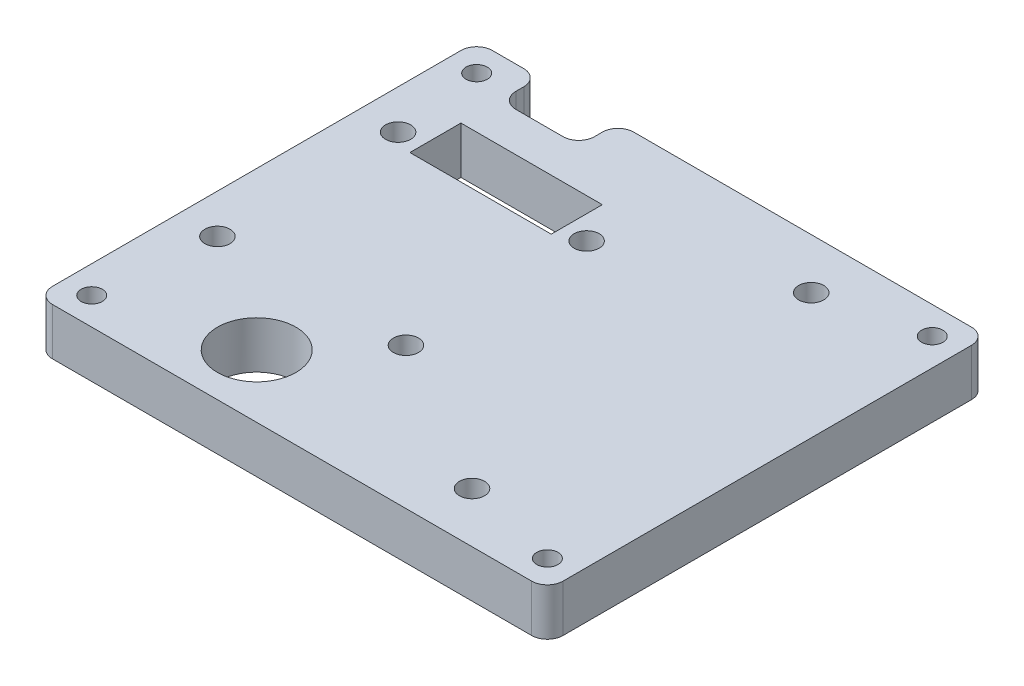
SolidWorks part; units mm, degrees
ref_plane "前视基准面" through (0, 0, 0) normal (0, 0, 1) x (1, 0, 0)
ref_plane "上视基准面" through (0, 0, 0) normal (0, 1, 0) x (1, 0, 0)
ref_plane "右视基准面" through (0, 0, 0) normal (1, 0, 0) x (0, 0, -1)
other "Configuration Table"
sketch "草图1" plane through (0, 0, 0) normal (0, 1, 0) x (1, 0, 0)
  line L1 (-32.5, -28) -> (32.5, -28)
  line L2 (-32.5, -28) -> (-32.5, 28)
  line L3 (-32.5, 28) -> (32.5, 28)
  line L4 (32.5, -28) -> (32.5, 28)
  line L5 (-32.5, -28) -> (32.5, 28) construction
  line L6 (-32.5, 28) -> (32.5, -28) construction
  point P0 (0, 0)
  dimension "D1" = 56
  dimension "D2" = 65
extrude "凸台-拉伸1" add sketch "草图1" along normal blind 6
sketch "草图2" plane through (0, 6, 0) normal (0, 1, 0) x (1, 0, 0)
  line L0 (-34.5459, 0) -> (41.9714, 0) construction
  line L1 (0, 29.3248) -> (0, -30.079) construction
  circle A0 centre (-29, 24.5) radius 1.35
  circle A1 centre (29, 24.5) radius 1.35
  circle A2 centre (29, -24.5) radius 1.35
  circle A3 centre (-29, -24.5) radius 1.35
  dimension "D1" = 2.7
  dimension "D2" = 58
  dimension "D3" = 49
extrude "切除-拉伸1" cut sketch "草图2" against normal up to surface (6 mm away) up to face at (0, 0, 0)
fillet "圆角2" radius 2 4 edges at (32.5, 3, -28) (32.5, 3, 28) (-32.5, 3, 28) (-32.5, 3, -28)
sketch "草图5" plane through (0, 6, 0) normal (0, 1, 0) x (1, 0, 0)
  line L0 (-32.5, 26) -> (-32.5, -26) construction
  line L2 (30.5, 28) -> (-30.5, 28) construction
  circle A0 centre (-27.5, 13) radius 1.6
  circle A1 centre (-3.5, 13) radius 1.6
  circle A2 centre (-27.5, -10) radius 1.6
  circle A4 centre (-3.5, -10) radius 1.6
  dimension "D1" = 3.2
  dimension "D2" = 3.2
  dimension "D3" = 23
  dimension "D4" = 24
  dimension "D5" = 15
  dimension "D6" = 5
  dimension "D7" = 3.2
  dimension "D8" = 3.2
extrude "切除-拉伸3" cut sketch "草图5" against normal up to surface (6 mm away) up to face at (-29, 0, 23.15)
sketch "草图7" plane through (0, 6, 0) normal (0, 1, 0) x (1, 0, 0)
  line L0 (-5.4241, 0) -> (43.0736, 0) construction
  line L2 (4.5, 12.5) -> (4.5, -12.5) construction
  line L4 (28.5, 12.5) -> (28.5, -12.5) construction
  line L5 (4.5, 12.5) -> (28.5, -12.5) construction
  line L6 (4.5, -12.5) -> (28.5, 12.5) construction
  line L7 (32.5, -26) -> (32.5, 26) construction
  line L8 (4.5, 0) -> (28.5, 0) construction
  arc A0 (28.5, 12.5) -> (4.5, 12.5) centre (16.5, 12.5) ccw construction
  arc A1 (28.5, -12.5) -> (4.5, -12.5) centre (16.5, -12.5) cw construction
  circle A2 centre (16.5, 21.59) radius 1.6
  circle A3 centre (16.5, -21.59) radius 1.6
  point P0 (16.5, 0)
  dimension "D4" = 3.2
  dimension "D5" = 43.18
  dimension "D1" = 12
  dimension "D2" = 25
  dimension "D3" = 4
extrude "切除-拉伸4" cut sketch "草图7" against normal up to surface (6 mm away) up to face at (-3.5, 0, -14.6)
sketch "草图8" plane through (0, 6, 0) normal (0, 1, 0) x (1, 0, 0)
  line L0 (-30.5, -28) -> (30.5, -28) construction
  line L1 (-32.5, 26) -> (-32.5, -26) construction
  circle A0 centre (-12.5, -20) radius 5
  dimension "D1" = 10
  dimension "D2" = 8
  dimension "D3" = 20
extrude "切除-拉伸5" cut sketch "草图8" against normal up to surface (6 mm away) up to face at (16.5, 0, -23.19)
sketch "草图9" plane through (0, 6, 0) normal (0, 1, 0) x (1, 0, 0)
  line L0 (-27.5, 13) -> (-3.5, 13) construction
  line L1 (-15.5, 13) -> (-15.5, 16.5) construction
  line L3 (-24.5, 11.5) -> (-6.5, 11.5)
  line L4 (-24.5, 11.5) -> (-24.5, 18)
  line L5 (-24.5, 18) -> (-6.5, 18)
  line L6 (-6.5, 11.5) -> (-6.5, 18)
  line L7 (-24.5, 11.5) -> (-6.5, 18) construction
  line L8 (-24.5, 18) -> (-6.5, 11.5) construction
  circle A0 centre (-27.5, 13) radius 1.6 construction
  point P6 (-15.5, 14.75)
  dimension "D1" = 3
  dimension "D2" = 5
  dimension "D3" = 1.5
extrude "切除-拉伸6" cut sketch "草图9" against normal up to surface (6 mm away) up to face at (-12.5, 0, 15)
sketch "草图10" plane through (0, 6, 0) normal (0, 1, 0) x (1, 0, 0)
  line L0 (30.5, 28) -> (-30.5, 28) construction
  line L1 (-24.5, 28) -> (-14.5, 28)
  line L2 (-24.5, 28) -> (-24.5, 23)
  line L3 (-24.5, 23) -> (-14.5, 23)
  line L4 (-14.5, 28) -> (-14.5, 23)
  line L5 (-24.5, 18) -> (-24.5, 11.5) construction
  line L6 (-6.5, 11.5) -> (-6.5, 18) construction
  dimension "D1" = 5
  dimension "D2" = 8
extrude "切除-拉伸7" cut sketch "草图10" against normal up to surface (6 mm away) up to face at (-15.5, 0, -14.75)
fillet "圆角3" radius 2 4 edges at (-24.5, 3, -28) (-24.5, 3, -23) (-14.5, 3, -23) (-14.5, 3, -28)
